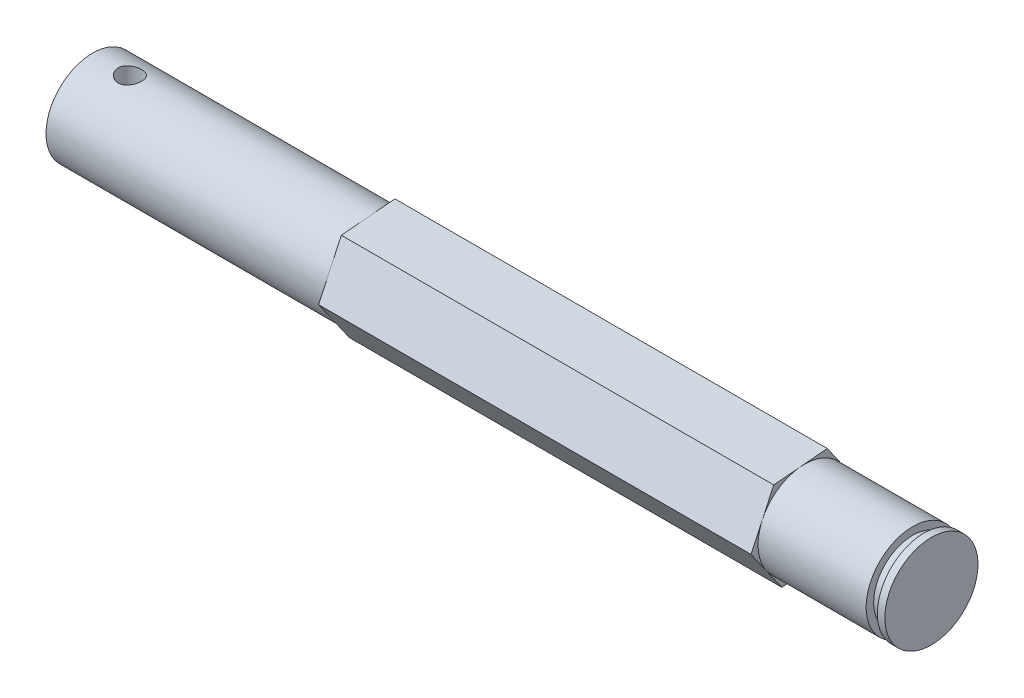
SolidWorks part; units mm, degrees
material "Plain Carbon Steel"
ref_plane "Front Plane" through (0, 0, 0) normal (0, 0, 1) x (1, 0, 0)
ref_plane "Top Plane" through (0, 0, 0) normal (0, 1, 0) x (1, 0, 0)
ref_plane "Right Plane" through (0, 0, 0) normal (1, 0, 0) x (0, 0, -1)
sketch "Sketch1" plane through (0, 0, 0) normal (1, 0, 0) x (0, 0, -1)
  line L1 (2.105, -3.0016) -> (3.652, 0.3222)
  line L2 (3.652, 0.3222) -> (1.547, 3.3238)
  line L3 (1.547, 3.3238) -> (-2.105, 3.0016)
  line L4 (-2.105, 3.0016) -> (-3.652, -0.3222)
  line L5 (-3.652, -0.3222) -> (-1.547, -3.3238)
  line L6 (-1.547, -3.3238) -> (2.105, -3.0016)
  circle A0 centre (0, 0) radius 3.175 construction
  dimension "D1" = 6.35
extrude "Boss-Extrude1" add sketch "Sketch1" along normal blind 38.1
sketch "Sketch2" plane through (38.1, 0, 0) normal (1, 0, 0) x (0, 0, -1)
  circle A0 centre (0, 0) radius 3.175
  dimension "D1" = 6.35
sketch "Sketch3" plane through (0, 0, 0) normal (-1, 0, 0) x (0, 0, 1)
  circle A0 centre (0, 0) radius 3.175
  dimension "D1" = 6.35
extrude "Boss-Extrude3" add sketch "Sketch3" along normal blind 19.05
sketch "Sketch4" plane through (0, 0, 0) normal (0, 1, 0) x (1, 0, 0)
  line L0 (-19.05, 3.175) -> (-19.05, -3.175) construction
  circle A0 centre (-16.51, 0) radius 0.7937
  dimension "D2" = 1.5875
  dimension "D1" = 2.54
extrude "Cut-Extrude1" cut sketch "Sketch4" along normal through all and the other way through all
sketch "Sketch5" plane through (38.1, 0, 0) normal (1, 0, 0) x (0, 0, -1)
  circle A0 centre (0, 0) radius 3.6662
  circle A1 centre (0, 0) radius 3.175
  line M2 (-1.547, -3.3238) -> (2.105, -3.0016)
  line M3 (2.105, -3.0016) -> (3.652, 0.3222)
  line M4 (3.652, 0.3222) -> (1.547, 3.3238)
  line M5 (1.547, 3.3238) -> (-2.105, 3.0016)
  line M6 (-2.105, 3.0016) -> (-3.652, -0.3222)
  line M7 (-3.652, -0.3222) -> (-1.547, -3.3238)
extrude "Cut-Extrude4" cut sketch "Sketch5" against normal blind 8.636 contours A0 M6 | A1 M6 M7 | A0 M7 | A1 M7 M2 | A0 M2 | A1 M2 M3 | A0 M3 | A1 M3 M4 | A0 M4 | A1 M4 M5 | A0 M5 | A1 M5 M6
ref_plane "Plane1" through (36.83, 0, 0) normal (1, 0, 0) x (0, 0, -1)
sketch "Sketch6" plane through (36.83, 0, 0) normal (1, 0, 0) x (0, 0, -1)
  circle A0 centre (0, 0) radius 2.667
  dimension "D1" = 5.334
extrude "Cut-Extrude5" cut sketch "Sketch6" along normal blind 0.762 flip side to cut
